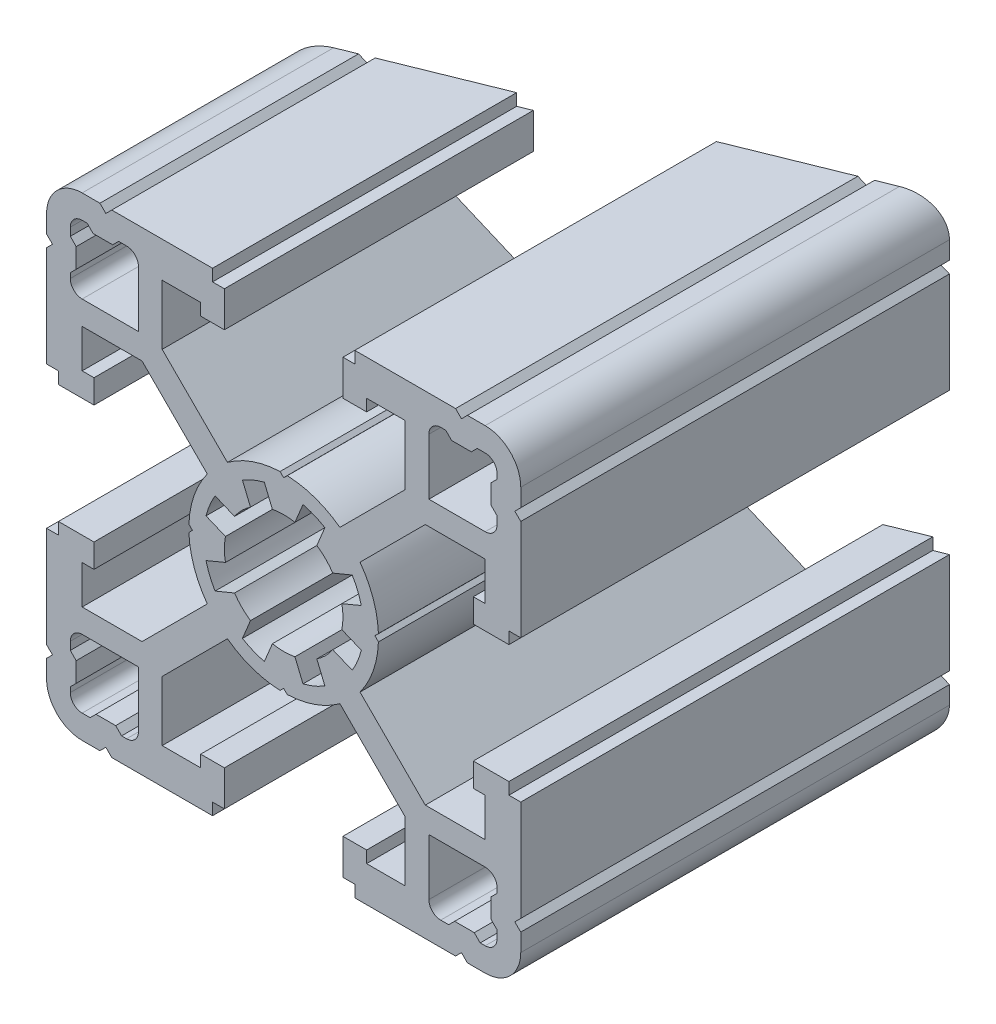
SolidWorks part; units mm, degrees
ref_plane "Front Plane" through (0, 0, 0) normal (0, 0, 1) x (1, 0, 0)
ref_plane "Top Plane" through (0, 0, 0) normal (0, 1, 0) x (1, 0, 0)
ref_plane "Right Plane" through (0, 0, 0) normal (1, 0, 0) x (0, 0, -1)
ref_plane "Plane1" through (0, 0, 100) normal (0, 0, 1) x (1, 0, 0)
sketch "Sketch1" plane through (0, 0, 100) normal (0, 0, 1) x (1, 0, 0)
  line L0 (17, 12.25) -> (12.25, 12.25)
  line L1 (12.25, 12.25) -> (12.25, 17)
  line L2 (13.25, 18) -> (13.6716, 18)
  line L3 (13.6716, 18) -> (14.1716, 17.5)
  line L4 (14.1716, 17.5) -> (15.8284, 17.5)
  line L5 (15.8284, 17.5) -> (16.3284, 18)
  line L6 (16.3284, 18) -> (17, 18)
  line L7 (18, 17) -> (18, 16.5784)
  line L8 (18, 16.5784) -> (17.5, 16.0784)
  line L9 (17.5, 16.0784) -> (17.5, 14.4216)
  line L10 (17.5, 14.4216) -> (18, 13.9216)
  line L11 (18, 13.9216) -> (18, 13.25)
  line L12 (-17, -12.25) -> (-12.25, -12.25)
  line L13 (-12.25, -12.25) -> (-12.25, -17)
  line L14 (-13.25, -18) -> (-13.6716, -18)
  line L15 (-13.6716, -18) -> (-14.1716, -17.5)
  line L16 (-14.1716, -17.5) -> (-15.8284, -17.5)
  line L17 (-15.8284, -17.5) -> (-16.3284, -18)
  line L18 (-16.3284, -18) -> (-17, -18)
  line L19 (-18, -17) -> (-18, -16.5784)
  line L20 (-18, -16.5784) -> (-17.5, -16.0784)
  line L21 (-17.5, -16.0784) -> (-17.5, -14.4216)
  line L22 (-17.5, -14.4216) -> (-18, -13.9216)
  line L23 (-18, -13.9216) -> (-18, -13.25)
  line L24 (-6, 19) -> (-6, 20)
  line L25 (-6, 20) -> (-14.5, 20)
  line L26 (-14.5, 20) -> (-15, 19.5)
  line L27 (-15, 19.5) -> (-15.5, 20)
  line L28 (-15.5, 20) -> (-17, 20)
  line L29 (-20, 17) -> (-20, 15.5)
  line L30 (-20, 15.5) -> (-19.5, 15)
  line L31 (-19.5, 15) -> (-20, 14.5)
  line L32 (-20, 14.5) -> (-20, 6)
  line L33 (-20, 6) -> (-19, 6)
  line L34 (-19, 6) -> (-19, 5)
  line L35 (-19, 5) -> (-16, 5)
  line L36 (-16, 5) -> (-16, 7)
  line L37 (-16, 7) -> (-17, 7)
  line L38 (-17, 7) -> (-17, 10.25)
  line L39 (-17, 10.25) -> (-11.9471, 10.25)
  line L40 (-11.9471, 10.25) -> (-6.4414, 4.7443)
  line L41 (-7.9941, 0.3064) -> (-7.7, 0)
  line L42 (-7.7, 0) -> (-7.9941, -0.3064)
  line L43 (-6.4414, -4.7443) -> (-11.9471, -10.25)
  line L44 (-11.9471, -10.25) -> (-17, -10.25)
  line L45 (-17, -10.25) -> (-17, -7)
  line L46 (-17, -7) -> (-16, -7)
  line L47 (-16, -7) -> (-16, -5)
  line L48 (-16, -5) -> (-19, -5)
  line L49 (-19, -5) -> (-19, -6)
  line L50 (-19, -6) -> (-20, -6)
  line L51 (-20, -6) -> (-20, -14.5)
  line L52 (-20, -14.5) -> (-19.5, -15)
  line L53 (-19.5, -15) -> (-20, -15.5)
  line L54 (-20, -15.5) -> (-20, -17)
  line L55 (-17, -20) -> (-15.5, -20)
  line L56 (-15.5, -20) -> (-15, -19.5)
  line L57 (-15, -19.5) -> (-14.5, -20)
  line L58 (-14.5, -20) -> (-6, -20)
  line L59 (-6, -20) -> (-6, -19)
  line L60 (-6, -19) -> (-5, -19)
  line L61 (-5, -19) -> (-5, -16)
  line L62 (-5, -16) -> (-7, -16)
  line L63 (-7, -16) -> (-7, -17)
  line L64 (-7, -17) -> (-10.25, -17)
  line L65 (-10.25, -17) -> (-10.25, -11.9471)
  line L66 (-10.25, -11.9471) -> (-4.7443, -6.4414)
  line L67 (-0.3064, -7.9941) -> (0, -7.7)
  line L68 (0, -7.7) -> (0.3064, -7.9941)
  line L69 (4.7443, -6.4414) -> (10.25, -11.9471)
  line L70 (10.25, -11.9471) -> (10.25, -17)
  line L71 (10.25, -17) -> (7, -17)
  line L72 (7, -17) -> (7, -16)
  line L73 (7, -16) -> (5, -16)
  line L74 (5, -16) -> (5, -19)
  line L75 (5, -19) -> (6, -19)
  line L76 (6, -19) -> (6, -20)
  line L77 (6, -20) -> (14.5, -20)
  line L78 (14.5, -20) -> (15, -19.5)
  line L79 (15, -19.5) -> (15.5, -20)
  line L80 (15.5, -20) -> (17, -20)
  line L81 (20, -17) -> (20, -15.5)
  line L82 (20, -15.5) -> (19.5, -15)
  line L83 (19.5, -15) -> (20, -14.5)
  line L84 (20, -14.5) -> (20, -6)
  line L85 (20, -6) -> (19, -6)
  line L86 (19, -6) -> (19, -5)
  line L87 (19, -5) -> (16, -5)
  line L88 (16, -5) -> (16, -7)
  line L89 (16, -7) -> (17, -7)
  line L90 (17, -7) -> (17, -10.25)
  line L91 (17, -10.25) -> (11.9471, -10.25)
  line L92 (11.9471, -10.25) -> (6.4414, -4.7443)
  line L93 (7.9941, -0.3064) -> (7.7, 0)
  line L94 (7.7, 0) -> (7.9941, 0.3064)
  line L95 (6.4414, 4.7443) -> (11.9471, 10.25)
  line L96 (11.9471, 10.25) -> (17, 10.25)
  line L97 (17, 10.25) -> (17, 7)
  line L98 (17, 7) -> (16, 7)
  line L99 (16, 7) -> (16, 5)
  line L100 (16, 5) -> (19, 5)
  line L101 (19, 5) -> (19, 6)
  line L102 (19, 6) -> (20, 6)
  line L103 (20, 6) -> (20, 14.5)
  line L104 (20, 14.5) -> (19.5, 15)
  line L105 (19.5, 15) -> (20, 15.5)
  line L106 (20, 15.5) -> (20, 17)
  line L107 (17, 20) -> (15.5, 20)
  line L108 (15.5, 20) -> (15, 19.5)
  line L109 (15, 19.5) -> (14.5, 20)
  line L110 (14.5, 20) -> (6, 20)
  line L111 (6, 20) -> (6, 19)
  line L112 (6, 19) -> (5, 19)
  line L113 (5, 19) -> (5, 16)
  line L114 (5, 16) -> (7, 16)
  line L115 (7, 16) -> (7, 17)
  line L116 (7, 17) -> (10.25, 17)
  line L117 (10.25, 17) -> (10.25, 11.9471)
  line L118 (10.25, 11.9471) -> (4.7443, 6.4414)
  line L119 (0.3064, 7.9941) -> (0, 7.7)
  line L120 (0, 7.7) -> (-0.3064, 7.9941)
  line L121 (-4.7443, 6.4414) -> (-10.25, 11.9471)
  line L122 (-10.25, 11.9471) -> (-10.25, 17)
  line L123 (-10.25, 17) -> (-7, 17)
  line L124 (-7, 17) -> (-7, 16)
  line L125 (-7, 16) -> (-5, 16)
  line L126 (-5, 16) -> (-5, 19)
  line L127 (-5, 19) -> (-6, 19)
  line L128 (-12.25, 17) -> (-12.25, 12.25)
  line L129 (-12.25, 12.25) -> (-17, 12.25)
  line L130 (-18, 13.25) -> (-18, 13.6716)
  line L131 (-18, 13.6716) -> (-17.5, 14.1716)
  line L132 (-17.5, 14.1716) -> (-17.5, 15.8284)
  line L133 (-17.5, 15.8284) -> (-18, 16.3284)
  line L134 (-18, 16.3284) -> (-18, 17)
  line L135 (-17, 18) -> (-16.5784, 18)
  line L136 (-16.5784, 18) -> (-16.0784, 17.5)
  line L137 (-16.0784, 17.5) -> (-14.4216, 17.5)
  line L138 (-14.4216, 17.5) -> (-13.9216, 18)
  line L139 (-13.9216, 18) -> (-13.25, 18)
  line L140 (12.25, -17) -> (12.25, -12.25)
  line L141 (12.25, -12.25) -> (17, -12.25)
  line L142 (18, -13.25) -> (18, -13.6716)
  line L143 (18, -13.6716) -> (17.5, -14.1716)
  line L144 (17.5, -14.1716) -> (17.5, -15.8284)
  line L145 (17.5, -15.8284) -> (18, -16.3284)
  line L146 (18, -16.3284) -> (18, -17)
  line L147 (17, -18) -> (16.5784, -18)
  line L148 (16.5784, -18) -> (16.0784, -17.5)
  line L149 (16.0784, -17.5) -> (14.4216, -17.5)
  line L150 (14.4216, -17.5) -> (13.9216, -18)
  line L151 (13.9216, -18) -> (13.25, -18)
  line L152 (1.6307, -6.5501) -> (0.9509, -4.9088)
  line L153 (-0.9509, -4.9088) -> (-1.6307, -6.5501)
  line L154 (-3.4785, -5.7847) -> (-2.7986, -4.1434)
  line L155 (-4.1434, -2.7986) -> (-5.7847, -3.4785)
  line L156 (-6.5501, -1.6307) -> (-4.9088, -0.9509)
  line L157 (-4.9088, 0.9509) -> (-6.5501, 1.6307)
  line L158 (-5.7847, 3.4785) -> (-4.1434, 2.7986)
  line L159 (-2.7986, 4.1434) -> (-3.4785, 5.7847)
  line L160 (-1.6307, 6.5501) -> (-0.9509, 4.9088)
  line L161 (0.9509, 4.9088) -> (1.6307, 6.5501)
  line L162 (3.4785, 5.7847) -> (2.7986, 4.1434)
  line L163 (4.1434, 2.7986) -> (5.7847, 3.4785)
  line L164 (6.5501, 1.6307) -> (4.9088, 0.9509)
  line L165 (4.9088, -0.9509) -> (6.5501, -1.6307)
  line L166 (5.7847, -3.4785) -> (4.1434, -2.7986)
  line L167 (2.7986, -4.1434) -> (3.4785, -5.7847)
  line L168 (0, 0) -> (23.4896, 0) construction
  line L169 (0, 0) -> (0, 26.3352) construction
  arc A0 (18, 13.25) -> (17, 12.25) centre (17, 13.25) cw
  arc A1 (12.25, 17) -> (13.25, 18) centre (13.25, 17) cw
  arc A2 (17, 18) -> (18, 17) centre (17, 17) cw
  arc A3 (-18, -13.25) -> (-17, -12.25) centre (-17, -13.25) cw
  arc A4 (-12.25, -17) -> (-13.25, -18) centre (-13.25, -17) cw
  arc A5 (-17, -18) -> (-18, -17) centre (-17, -17) cw
  arc A6 (-17, 20) -> (-20, 17) centre (-17, 17) ccw
  arc A7 (-6.4414, 4.7443) -> (-7.9941, 0.3064) centre (0, 0) ccw
  arc A8 (-7.9941, -0.3064) -> (-6.4414, -4.7443) centre (0, 0) ccw
  arc A9 (-20, -17) -> (-17, -20) centre (-17, -17) ccw
  arc A10 (-4.7443, -6.4414) -> (-0.3064, -7.9941) centre (0, 0) ccw
  arc A11 (0.3064, -7.9941) -> (4.7443, -6.4414) centre (0, 0) ccw
  arc A12 (17, -20) -> (20, -17) centre (17, -17) ccw
  arc A13 (6.4414, -4.7443) -> (7.9941, -0.3064) centre (0, 0) ccw
  arc A14 (7.9941, 0.3064) -> (6.4414, 4.7443) centre (0, 0) ccw
  arc A15 (20, 17) -> (17, 20) centre (17, 17) ccw
  arc A16 (4.7443, 6.4414) -> (0.3064, 7.9941) centre (0, 0) ccw
  arc A17 (-0.3064, 7.9941) -> (-4.7443, 6.4414) centre (0, 0) ccw
  arc A18 (-13.25, 18) -> (-12.25, 17) centre (-13.25, 17) cw
  arc A19 (-17, 12.25) -> (-18, 13.25) centre (-17, 13.25) cw
  arc A20 (-18, 17) -> (-17, 18) centre (-17, 17) cw
  arc A21 (13.25, -18) -> (12.25, -17) centre (13.25, -17) cw
  arc A22 (17, -12.25) -> (18, -13.25) centre (17, -13.25) cw
  arc A23 (18, -17) -> (17, -18) centre (17, -17) cw
  arc A24 (3.4785, -5.7847) -> (1.6307, -6.5501) centre (0, 0) cw
  arc A25 (0.9509, -4.9088) -> (-0.9509, -4.9088) centre (0, 0) cw
  arc A26 (-1.6307, -6.5501) -> (-3.4785, -5.7847) centre (0, 0) cw
  arc A27 (-2.7986, -4.1434) -> (-4.1434, -2.7986) centre (0, 0) cw
  arc A28 (-5.7847, -3.4785) -> (-6.5501, -1.6307) centre (0, 0) cw
  arc A29 (-4.9088, -0.9509) -> (-4.9088, 0.9509) centre (0, 0) cw
  arc A30 (-6.5501, 1.6307) -> (-5.7847, 3.4785) centre (0, 0) cw
  arc A31 (-4.1434, 2.7986) -> (-2.7986, 4.1434) centre (0, 0) cw
  arc A32 (-3.4785, 5.7847) -> (-1.6307, 6.5501) centre (0, 0) cw
  arc A33 (-0.9509, 4.9088) -> (0.9509, 4.9088) centre (0, 0) cw
  arc A34 (1.6307, 6.5501) -> (3.4785, 5.7847) centre (0, 0) cw
  arc A35 (2.7986, 4.1434) -> (4.1434, 2.7986) centre (0, 0) cw
  arc A36 (5.7847, 3.4785) -> (6.5501, 1.6307) centre (0, 0) cw
  arc A37 (4.9088, 0.9509) -> (4.9088, -0.9509) centre (0, 0) cw
  arc A38 (6.5501, -1.6307) -> (5.7847, -3.4785) centre (0, 0) cw
  arc A39 (4.1434, -2.7986) -> (2.7986, -4.1434) centre (0, 0) cw
  dimension "D3" = 5
  dimension "D4" = 8
  dimension "D5" = 6.75
  dimension "D20" = 1
  dimension "D21" = 1
  dimension "D23" = 3
  dimension "D1" = 40
  dimension "D2" = 40
  dimension "D6" = 92.342
  dimension "D7" = 90
  dimension "D8" = 90
  dimension "D9" = 15
  dimension "D10" = 1
  dimension "D11" = 1
  dimension "D12" = 2
  dimension "D13" = 3.25
  dimension "D14" = 1
  dimension "D15" = 4
  dimension "D16" = 3
  dimension "D17" = 1
  dimension "D18" = 3.25
  dimension "D19" = 2.4
  dimension "D22" = 5
  dimension "D24" = 5
extrude "Boss-Extrude1" add sketch "Sketch1" against normal blind 100
sketch "Sketch2" plane through (0, 20, 0) normal (0, 1, 0) x (1, 0, 0)
  line L1 (-20, -80) -> (20, -63.839)
  line L2 (20, 0) -> (20, -100) construction
  line L5 (-20, -80) -> (-20, 0)
  line L6 (-20, 0) -> (20, 0)
  line L7 (20, 0) -> (20, -63.839)
  line L8 (-20, -80) -> (-20, -100) construction
  dimension "D1" = 68
  dimension "D2" = 20
extrude "Cut-Extrude1" cut sketch "Sketch2" against normal through all both and the other way through all
